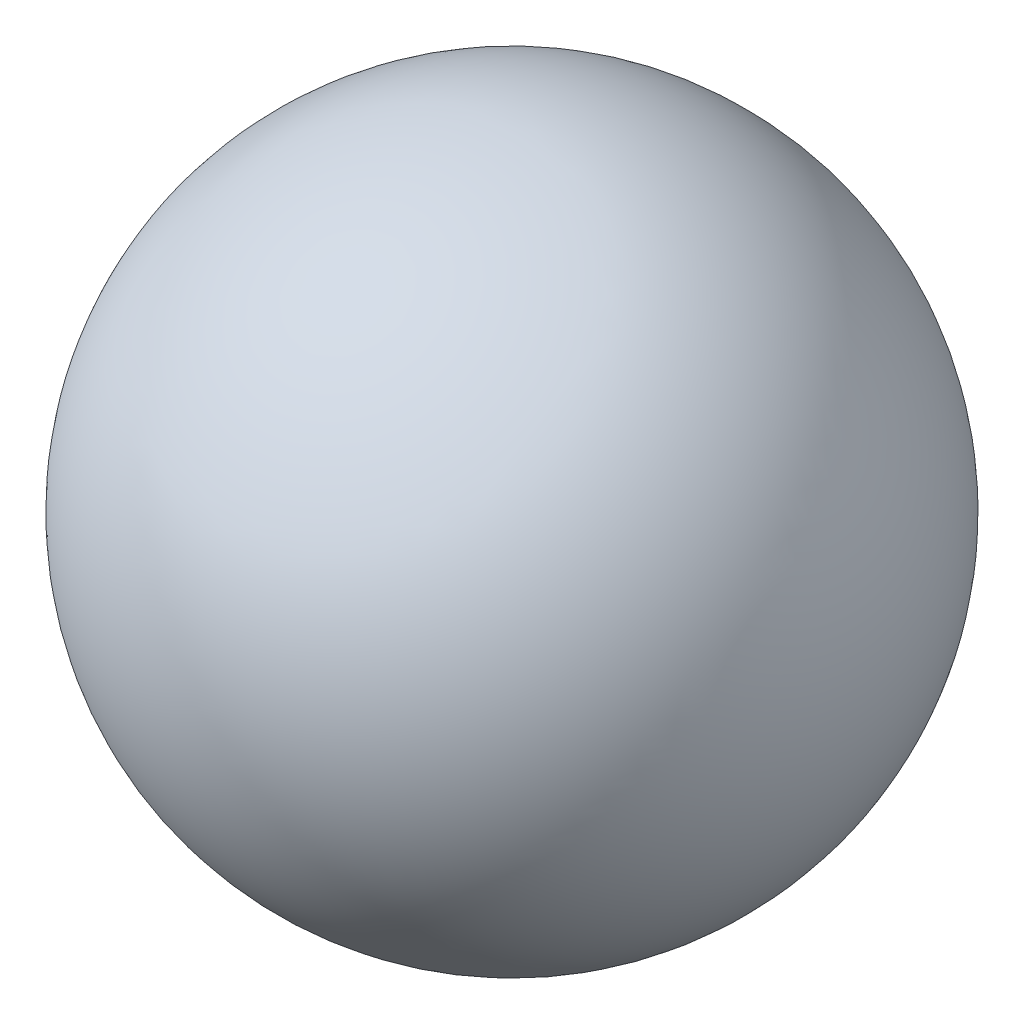
SolidWorks part; units mm, degrees
ref_plane "Front Plane" through (0, 0, 0) normal (0, 0, 1) x (1, 0, 0)
ref_plane "Top Plane" through (0, 0, 0) normal (0, 1, 0) x (1, 0, 0)
ref_plane "Right Plane" through (0, 0, 0) normal (1, 0, 0) x (0, 0, -1)
ref_plane "Plane1"
sketch "Sketch1" plane through (0, 0, 0) normal (0, 0, 1) x (1, 0, 0)
  line L0 (13.1595, 19.5) -> (2.8405, 19.5)
  line L1 (13.1595, 19.5) -> (2.8405, 19.5) construction
  arc A0 (13.1595, 19.5) -> (2.8405, 19.5) centre (8, 19.5) ccw
revolve "Revolução1" add sketch "Sketch1" angle 360 about L1
